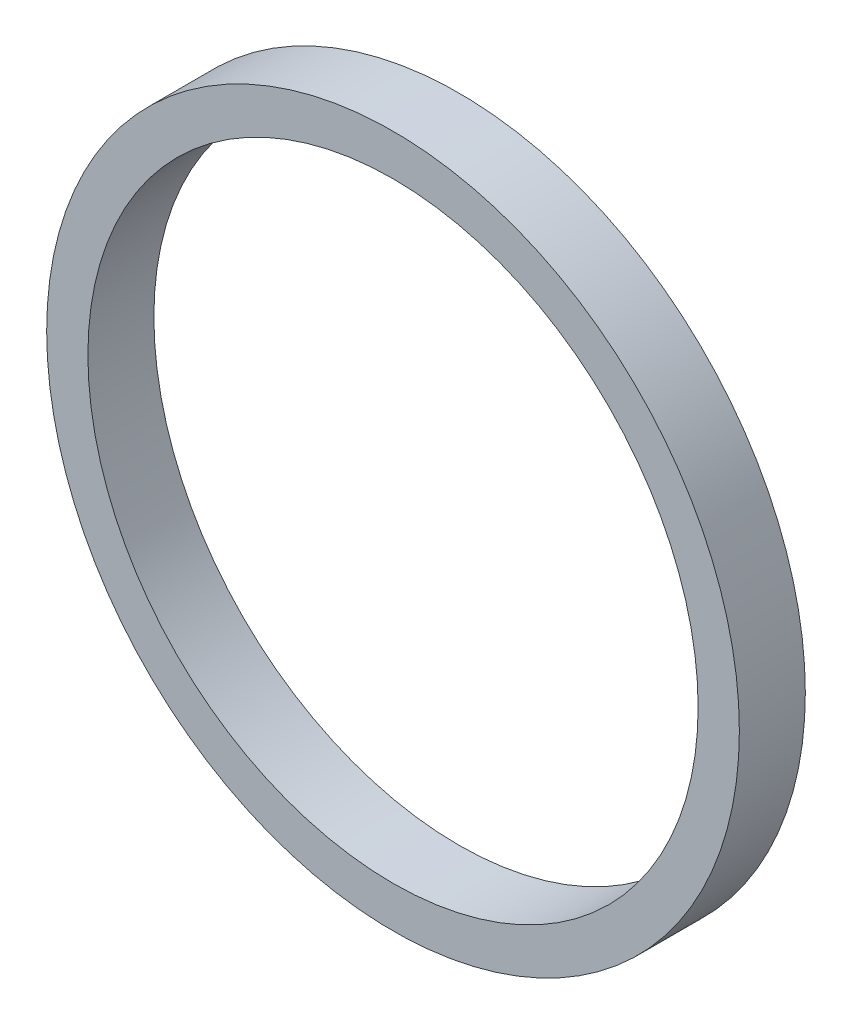
SolidWorks part; units mm, degrees
ref_plane "Ön Düzlem" through (0, 0, 0) normal (0, 0, 1) x (1, 0, 0)
ref_plane "Üst Düzlem" through (0, 0, 0) normal (0, 1, 0) x (1, 0, 0)
ref_plane "Sağ Düzlem" through (0, 0, 0) normal (1, 0, 0) x (0, 0, -1)
sketch "Çizim1" plane through (0, 0, 0) normal (0, 0, 1) x (1, 0, 0)
  circle A0 centre (0, 0) radius 1.85
  circle A1 centre (0, 0) radius 2.1
  dimension "D1" = 4.2
  dimension "D2" = 3.7
extrude "Yükseklik-Ekstrüzyon1" add sketch "Çizim1" along normal blind 0.4
